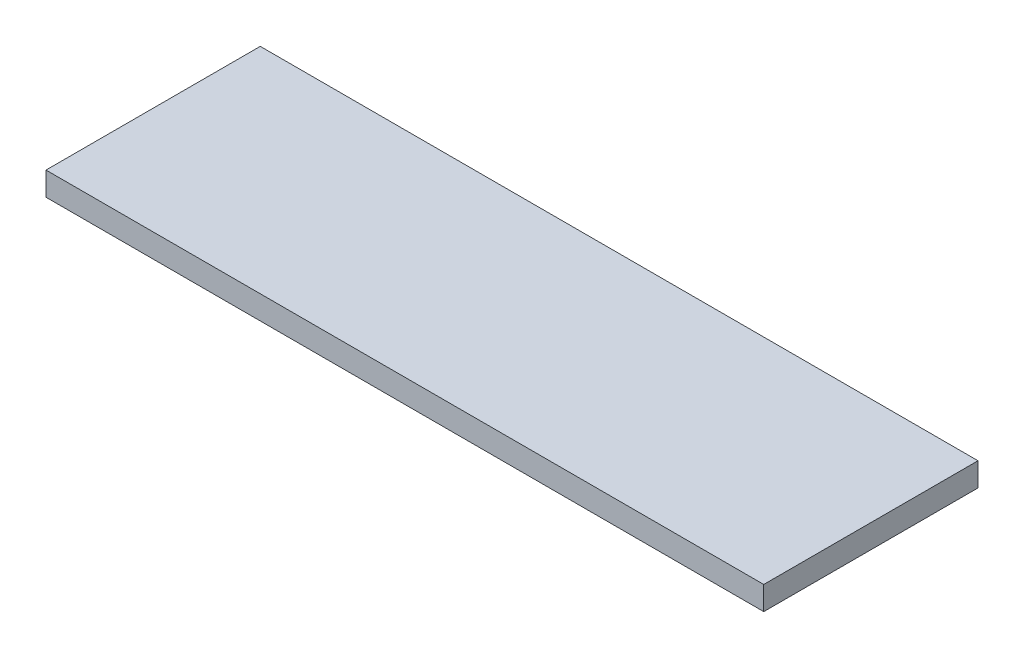
SolidWorks part; units mm, degrees
material "Pino"
ref_plane "Alzado" through (0, 0, 0) normal (0, 0, 1) x (1, 0, 0)
ref_plane "Planta" through (0, 0, 0) normal (0, 1, 0) x (1, 0, 0)
ref_plane "Vista lateral" through (0, 0, 0) normal (1, 0, 0) x (0, 0, -1)
sketch "Croquis1" plane through (0, 0, 0) normal (0, 1, 0) x (1, 0, 0)
  line L1 (-281.9277, -69.2771) -> (388.0723, -69.2771)
  line L2 (-281.9277, -69.2771) -> (-281.9277, 130.7229)
  line L3 (-281.9277, 130.7229) -> (388.0723, 130.7229)
  line L4 (388.0723, -69.2771) -> (388.0723, 130.7229)
  dimension "D1" = 200
  dimension "D2" = 670
extrude "Saliente-Extruir1" add sketch "Croquis1" along normal blind 22
